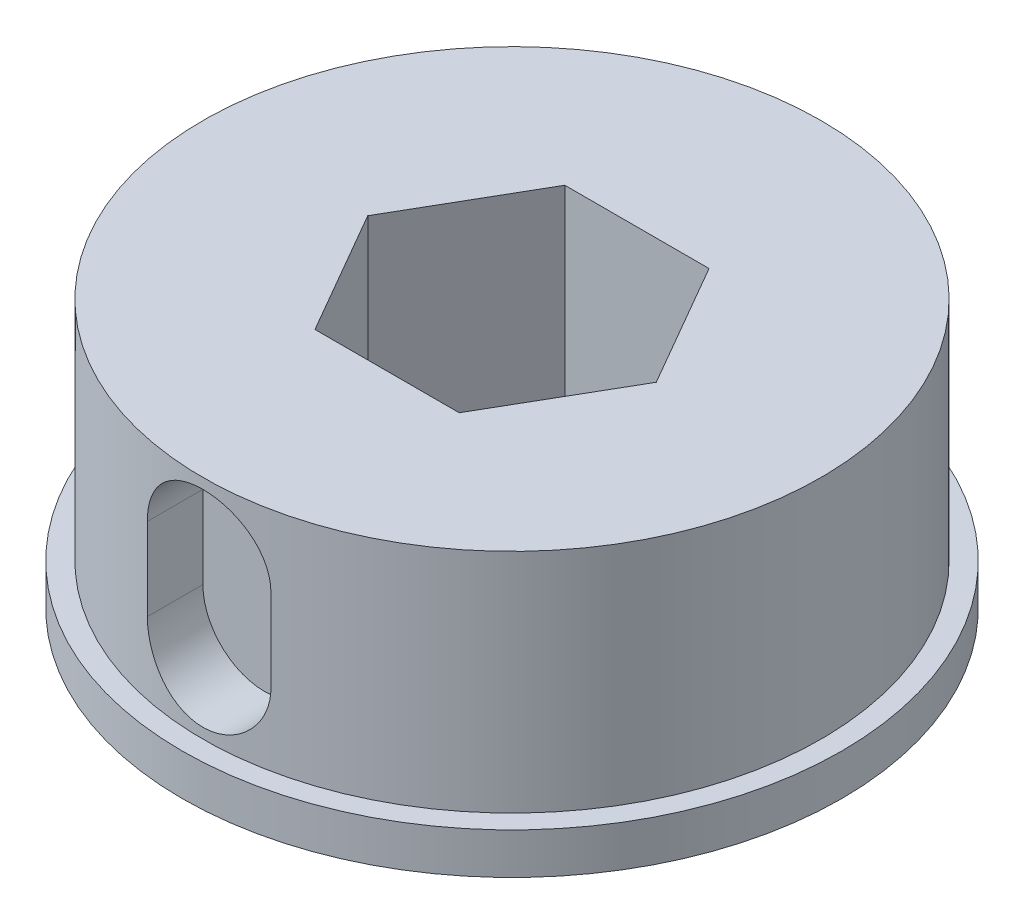
SolidWorks part; units mm, degrees
ref_plane "Front Plane" through (0, 0, 0) normal (0, 0, 1) x (1, 0, 0)
ref_plane "Top Plane" through (0, 0, 0) normal (0, 1, 0) x (1, 0, 0)
ref_plane "Right Plane" through (0, 0, 0) normal (1, 0, 0) x (0, 0, -1)
sketch "Sketch1" plane through (0, 0, 0) normal (0, 0, 1) x (1, 0, 0)
  line L0 (0, 0) -> (0, 13) construction
  line L1 (0, 13) -> (15, 13)
  line L2 (15, 13) -> (15, 2)
  line L3 (15, 2) -> (16, 2)
  line L4 (16, 2) -> (16, 0)
  line L5 (16, 0) -> (0, 0)
  line L6 (0, 0) -> (0, 13)
  dimension "D1" = 16
  dimension "D2" = 15
  dimension "D3" = 13
  dimension "D4" = 2
revolve "Revolve2" add sketch "Sketch1" angle 360 about L0
sketch "Sketch2" plane through (0, 13, 0) normal (0, 1, 0) x (1, 0, 0)
  line L0 (0, 7) -> (0, -7) construction
  line L1 (-7, 0) -> (-3.5, -6.0622)
  line L2 (-3.5, -6.0622) -> (3.5, -6.0622)
  line L3 (3.5, -6.0622) -> (7, 0)
  line L4 (7, 0) -> (3.5, 6.0622)
  line L5 (3.5, 6.0622) -> (-3.5, 6.0622)
  line L6 (-3.5, 6.0622) -> (-7, 0)
  circle A0 centre (0, 0) radius 7 construction
  circle A1 centre (0, 0) radius 7 construction
  dimension "D1" = 14
extrude "Cut-Extrude1" cut sketch "Sketch2" against normal through all
ref_plane "Plane1" through (0, 0, 15) normal (0, 0, 1) x (1, 0, 0)
sketch "Sketch4" plane through (0, 0, 15) normal (0, 0, 1) x (1, 0, 0)
  line L0 (0, 13) -> (0, 2) construction
  line L1 (15, 13) -> (-15, 13) construction
  line L2 (16, 2) -> (-16, 2) construction
  line L3 (0, 9.5) -> (0, 5.5) construction
  line L4 (3, 9.5) -> (3, 5.5)
  line L5 (-3, 9.5) -> (-3, 5.5)
  arc A0 (3, 9.5) -> (-3, 9.5) centre (0, 9.5) ccw
  arc A1 (-3, 5.5) -> (3, 5.5) centre (0, 5.5) ccw
  point P8 (0, 7.5)
  dimension "D2" = 3
  dimension "D1" = 4
extrude "Cut-Extrude2" cut sketch "Sketch4" against normal blind 3
